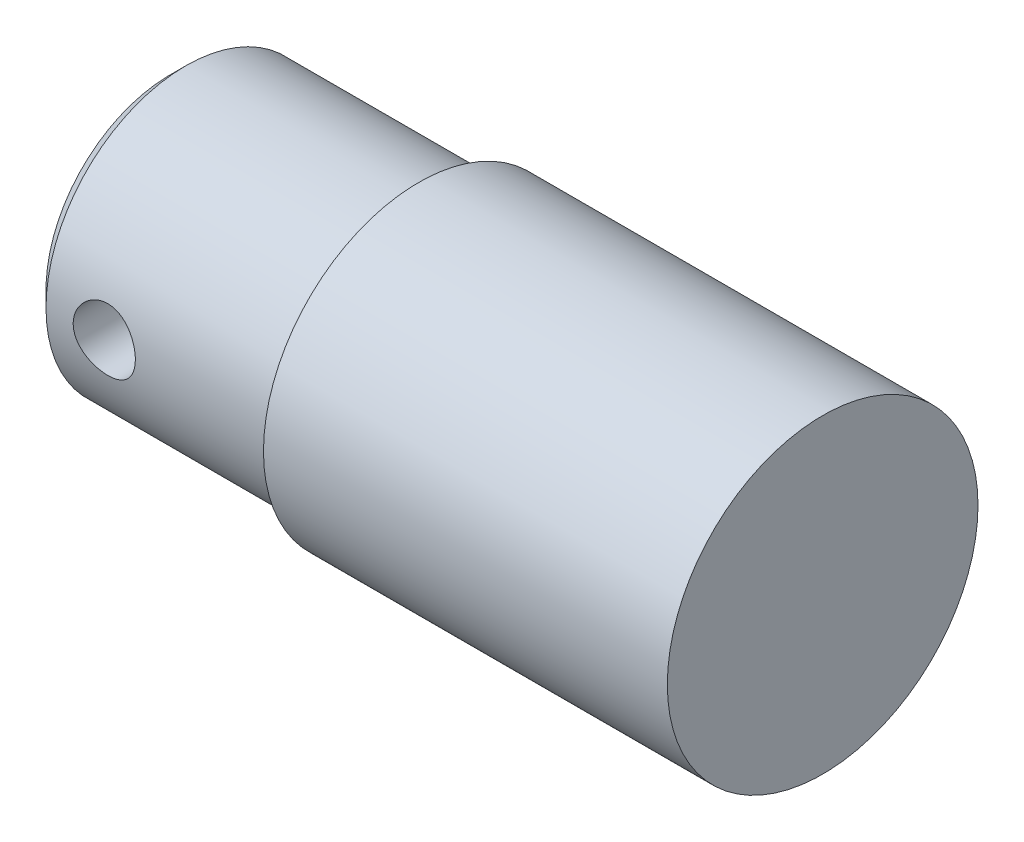
SolidWorks part; units mm, degrees
material "C40 or 38NiCrMo4"
ref_plane "Piano frontale" through (0, 0, 0) normal (0, 0, 1) x (1, 0, 0)
ref_plane "Piano superiore" through (0, 0, 0) normal (0, 1, 0) x (1, 0, 0)
ref_plane "Piano destro" through (0, 0, 0) normal (1, 0, 0) x (0, 0, -1)
sketch "Schizzo1" plane through (0, 0, 0) normal (1, 0, 0) x (0, 0, -1)
  circle A0 centre (0, 0) radius 20
extrude "Estrusione1" add sketch "Schizzo1" along normal blind 52
sketch "Schizzo2" plane through (0, 0, 0) normal (-1, 0, 0) x (0, 0, 1)
  circle A0 centre (0, 0) radius 18
extrude "Estrusione2" add sketch "Schizzo2" along normal blind 32
sketch "Schizzo5" plane through (0, 0, 0) normal (0, 0, 1) x (1, 0, 0)
  line L0 (0, 0) -> (-38.9025, 0) construction
  line L1 (0, 20) -> (0, -20) construction
  circle A0 centre (-22.5, 0) radius 4
  dimension "D1" = 22.5
extrude "Estrusione5" cut sketch "Schizzo5" against normal through all and the other way through all
chamfer "Smusso2" distance 2 angle 45 1 edges at (-32, 0, 18)
sketch "Schizzo3" plane through (-32, 0, 0) normal (-1, 0, 0) x (0, 0, 1)
  circle A0 centre (0, 0) radius 17
extrude "Estrusione3" add sketch "Schizzo3" along normal blind 2
sketch "Schizzo4" plane through (-34, 0, 0) normal (-1, 0, 0) x (0, 0, 1)
  circle A0 centre (0, 0) radius 18
extrude "Estrusione4" add sketch "Schizzo4" along normal blind 4
chamfer "Smusso1" distance 2 angle 45 1 edges at (-38, 0, 18)
sketch "Schizzo6" plane through (-32, 0, 0) normal (1, 0, 0) x (0, 0, -1)
  circle A0 centre (0, 0) radius 24.0718
extrude "Estrusione6" cut sketch "Schizzo6" against normal blind 10
